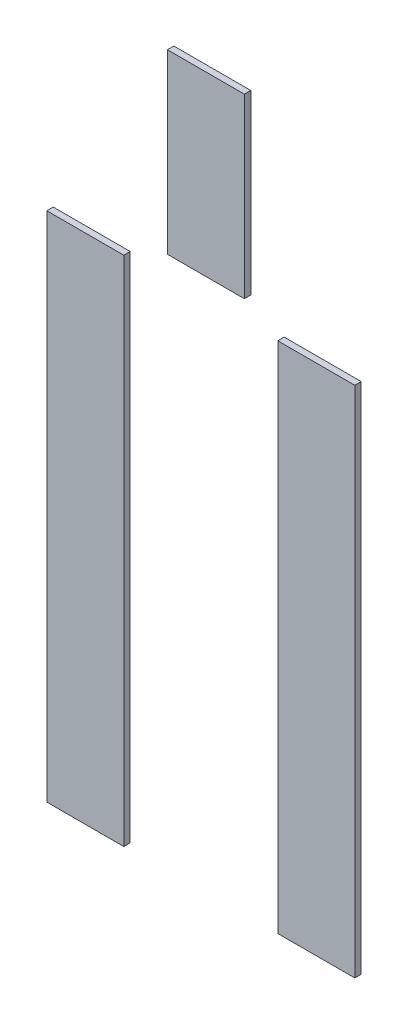
SolidWorks part; units mm, degrees
ref_plane "Спереди" through (0, 0, 0) normal (0, 0, 1) x (1, 0, 0)
ref_plane "Сверху" through (0, 0, 0) normal (0, 1, 0) x (1, 0, 0)
ref_plane "Справа" through (0, 0, 0) normal (1, 0, 0) x (0, 0, -1)
sketch "Эскиз1" plane through (0, 0, 0) normal (0, 0, 1) x (1, 0, 0)
  line L0 (43.2291, 435.023) -> (163.2291, 435.023)
  line L1 (-316.8176, 430.5629) -> (-196.8176, 430.5629)
  line L2 (-316.8176, 430.5629) -> (-316.8176, -367.5964)
  line L3 (-316.8176, -367.5964) -> (-196.8176, -367.5964)
  line L4 (-196.8176, 430.5629) -> (-196.8176, -367.5964)
  line L5 (43.2291, 435.023) -> (43.2291, -364.977)
  line L6 (43.2291, -364.977) -> (163.2291, -364.977)
  line L7 (163.2291, 435.023) -> (163.2291, -364.977)
  line L8 (-128.8705, 741.8642) -> (-8.8705, 741.8642)
  line L9 (-128.8705, 741.8642) -> (-128.8705, 465.7604)
  line L10 (-128.8705, 465.7604) -> (-8.8705, 465.7604)
  line L11 (-8.8705, 741.8642) -> (-8.8705, 465.7604)
extrude "Бобышка-Вытянуть3" add sketch "Эскиз1" along normal blind 10
